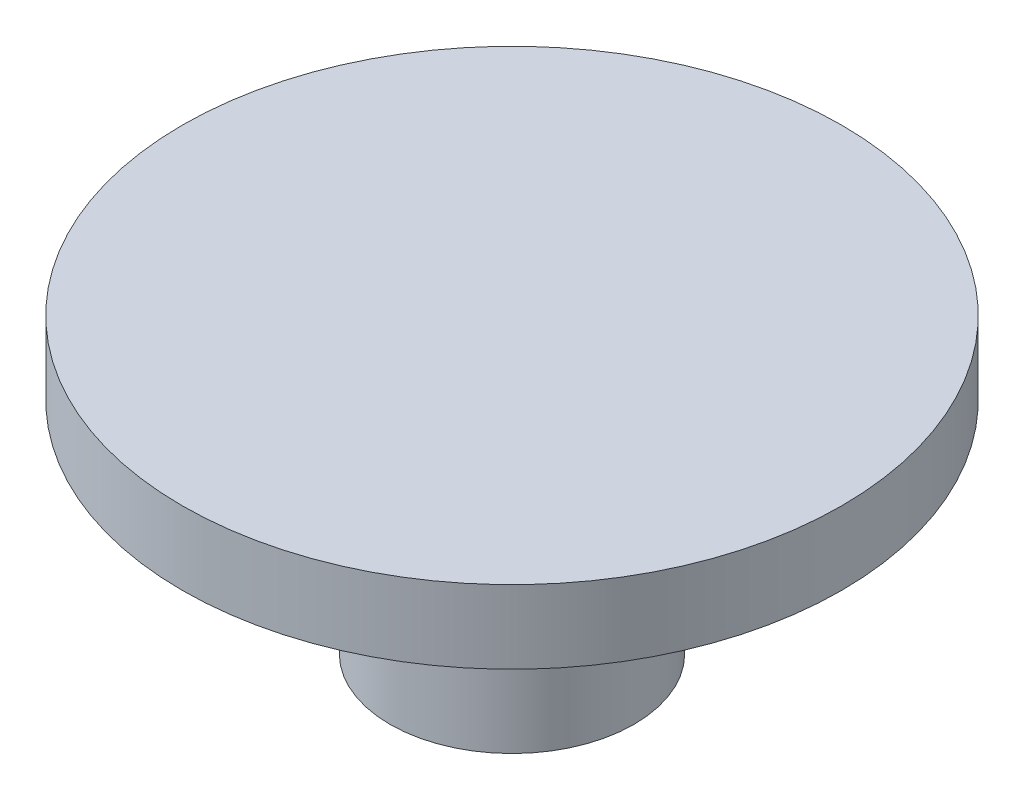
SolidWorks part; units mm, degrees
ref_plane "Front Plane" through (0, 0, 0) normal (0, 0, 1) x (1, 0, 0)
ref_plane "Top Plane" through (0, 0, 0) normal (0, 1, 0) x (1, 0, 0)
ref_plane "Right Plane" through (0, 0, 0) normal (1, 0, 0) x (0, 0, -1)
sketch "Sketch1" plane through (0, 0, 0) normal (0, 0, 1) x (1, 0, 0)
  line L0 (0, 0) -> (0, 12) construction
  line L1 (0, 0) -> (5, 0)
  line L2 (5, 0) -> (5, 9)
  line L3 (5, 9) -> (13.5, 9)
  line L4 (13.5, 9) -> (13.5, 12)
  line L5 (13.5, 12) -> (0, 12)
  line L6 (0, 12) -> (0, 0)
  dimension "D1" = 5
  dimension "D2" = 13.5
  dimension "D3" = 12
  dimension "D4" = 3
revolve "Revolve1" add sketch "Sketch1" angle 360 about L6
equation "\"Housing_OD\"= 45mm"
equation "\"Housing_Wall\"= 1.5mm"
equation "\"Stack_ID\"= 28mm"
equation "\"Ampoule_OD\"= 25.5mm"
equation "\"Cell_Height\"= 1.66mm"
